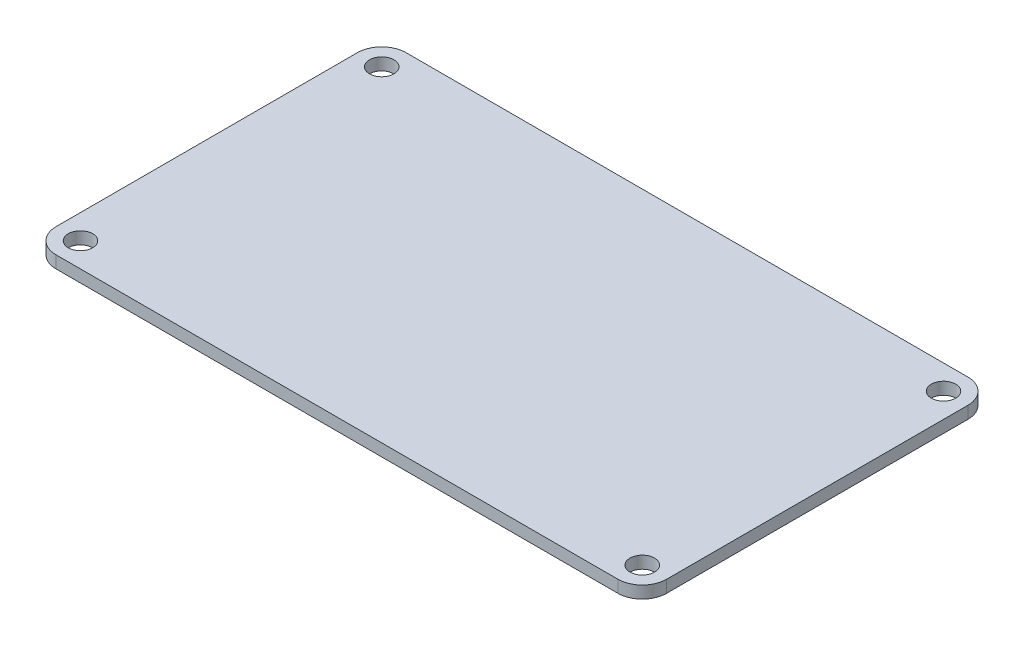
SolidWorks part; units mm, degrees
ref_plane "前视基准面" through (0, 0, 0) normal (0, 0, 1) x (1, 0, 0)
ref_plane "上视基准面" through (0, 0, 0) normal (0, 1, 0) x (1, 0, 0)
ref_plane "右视基准面" through (0, 0, 0) normal (1, 0, 0) x (0, 0, -1)
sketch "Sketch1" plane through (0, 0, 0) normal (0, 1, 0) x (1, 0, 0)
  line L0 (-37.5, 0) -> (37.5, 0) construction
  line L1 (34.5, -21.5) -> (-34.5, -21.5)
  line L2 (37.5, -18.5) -> (37.5, 18.5)
  line L3 (34.5, 21.5) -> (-34.5, 21.5)
  line L4 (-37.5, -18.5) -> (-37.5, 18.5)
  line L5 (0, 21.5) -> (0, -21.5) construction
  arc A0 (34.5, -21.5) -> (37.5, -18.5) centre (34.5, -18.5) ccw
  arc A1 (37.5, 18.5) -> (34.5, 21.5) centre (34.5, 18.5) ccw
  arc A2 (-34.5, -21.5) -> (-37.5, -18.5) centre (-34.5, -18.5) cw
  arc A3 (-34.5, 21.5) -> (-37.5, 18.5) centre (-34.5, 18.5) ccw
  circle A4 centre (-34.5, 18.5) radius 1.5
  circle A5 centre (34.5, 18.5) radius 1.5
  circle A6 centre (-34.5, -18.5) radius 1.5
  circle A7 centre (34.5, -18.5) radius 1.5
  point P0 (0, 0)
  point P15 (37.5, 21.5)
  point P18 (-37.5, -21.5)
  point P21 (-37.5, 21.5)
  dimension "D3" = 3
  dimension "D1" = 75
  dimension "D2" = 43
extrude "Boss-Extrude1" add sketch "Sketch1" along normal blind 1.5
